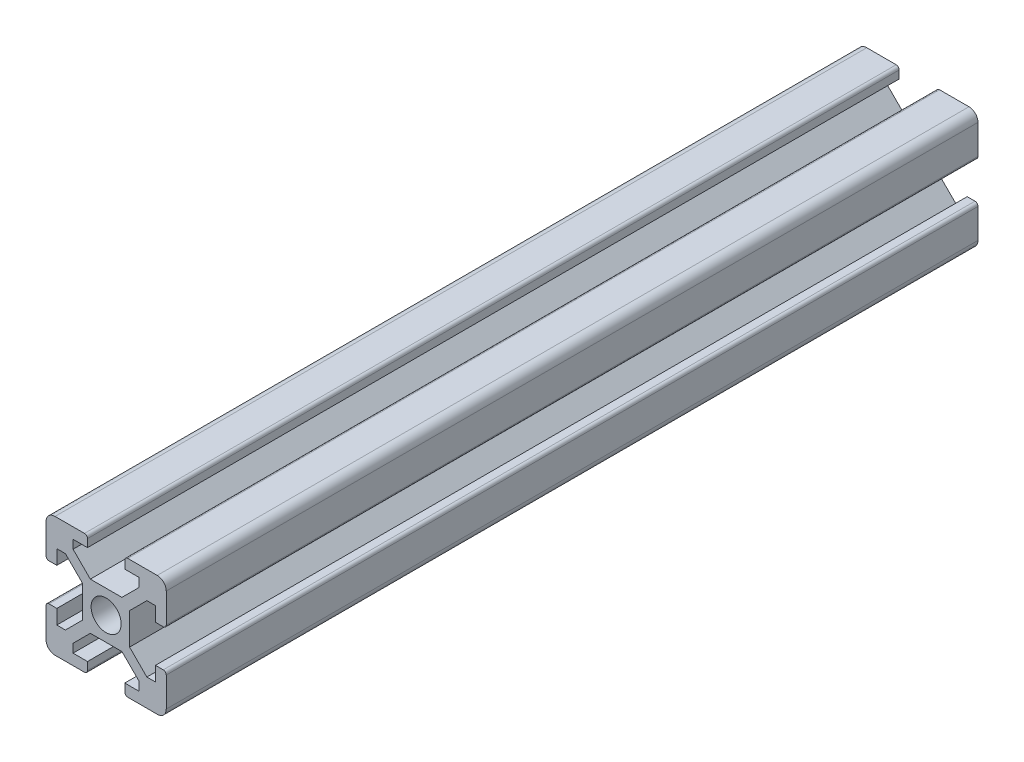
SolidWorks part; units mm, degrees
ref_plane "前视基准面" through (0, 0, 0) normal (0, 0, 1) x (1, 0, 0)
ref_plane "上视基准面" through (0, 0, 0) normal (0, 1, 0) x (1, 0, 0)
ref_plane "右视基准面" through (0, 0, 0) normal (1, 0, 0) x (0, 0, -1)
sketch "草图1" plane through (0, 0, 0) normal (0, 0, 1) x (1, 0, 0)
  line L0 (0, 6.9) -> (0, 0)
  line L1 (20, 20) -> (20, 13.1)
  line L2 (1.8, 15.5) -> (3.2272, 15.5)
  line L3 (4.5, 16.7728) -> (4.5, 18.2)
  line L4 (0, 13.1) -> (0, 20)
  line L5 (6.9, 20) -> (6.9, 18.2)
  line L6 (6.9, 18.2) -> (4.5, 18.2)
  line L7 (13.1, 20) -> (20, 20)
  line L8 (6.9, 20) -> (0, 20)
  line L9 (0, 0) -> (6.9, 0)
  line L10 (13.1, 0) -> (20, 0)
  line L11 (15.5, 18.2) -> (15.5, 16.7728)
  line L12 (16.7728, 15.5) -> (18.2, 15.5)
  line L13 (20, 6.9) -> (20, 0)
  line L14 (1.8, 4.5) -> (3.2272, 4.5)
  line L15 (4.5, 3.2272) -> (4.5, 1.8)
  line L16 (12.6272, 6.1) -> (15.5, 3.2272)
  line L17 (18.2, 4.5) -> (16.7728, 4.5)
  line L18 (15.5, 3.2272) -> (15.5, 1.8)
  line L19 (13.9, 7.3728) -> (16.7728, 4.5)
  line L20 (13.1, 20) -> (13.1, 18.2)
  line L21 (13.1, 18.2) -> (15.5, 18.2)
  line L22 (7.3728, 13.9) -> (12.6272, 13.9)
  line L23 (13.9, 12.6272) -> (13.9, 7.3728)
  line L24 (7.3728, 6.1) -> (12.6272, 6.1)
  line L25 (6.1, 12.6272) -> (6.1, 7.3728)
  line L27 (12.6272, 13.9) -> (15.5, 16.7728)
  line L30 (3.2272, 4.5) -> (6.1, 7.3728)
  line L32 (4.5, 3.2272) -> (7.3728, 6.1)
  line L33 (20, 13.1) -> (18.2, 13.1)
  line L34 (18.2, 13.1) -> (18.2, 15.5)
  line L36 (20, 6.9) -> (18.2, 6.9)
  line L37 (18.2, 6.9) -> (18.2, 4.5)
  line L39 (13.1, 0) -> (13.1, 1.8)
  line L40 (13.1, 1.8) -> (15.5, 1.8)
  line L42 (6.9, 0) -> (6.9, 1.8)
  line L43 (6.9, 1.8) -> (4.5, 1.8)
  line L45 (0, 6.9) -> (1.8, 6.9)
  line L46 (1.8, 6.9) -> (1.8, 4.5)
  line L48 (0, 13.1) -> (1.8, 13.1)
  line L49 (1.8, 13.1) -> (1.8, 15.5)
  line L50 (4.5, 16.7728) -> (7.3728, 13.9)
  line L51 (3.2272, 15.5) -> (6.1, 12.6272)
  line L53 (13.9, 12.6272) -> (16.7728, 15.5)
  line L62 (1.8, 13.1) -> (1.8, 15.5)
  line L63 (0, 13.1) -> (1.8, 13.1)
  line L66 (6.9, 18.2) -> (4.5, 18.2)
  line L67 (6.9, 20) -> (6.9, 18.2)
  line L68 (3.2272, 15.5) -> (1.8, 15.5)
  line L69 (4.5, 18.2) -> (4.5, 16.7728)
  line L75 (4.5, 1.8) -> (4.5, 3.2272)
  line L76 (3.2272, 4.5) -> (1.8, 4.5)
  line L77 (6.9, 0) -> (6.9, 1.8)
  line L78 (6.9, 1.8) -> (4.5, 1.8)
  line L80 (0, 6.9) -> (1.8, 6.9)
  line L81 (1.8, 6.9) -> (1.8, 4.5)
  line L90 (1.8, 6.9) -> (1.8, 4.5)
  line L91 (0, 6.9) -> (1.8, 6.9)
  line L93 (18.2, 6.9) -> (18.2, 4.5)
  line L94 (20, 6.9) -> (18.2, 6.9)
  line L98 (13.1, 1.8) -> (15.5, 1.8)
  line L99 (13.1, 0) -> (13.1, 1.8)
  line L100 (16.7728, 4.5) -> (18.2, 4.5)
  line L101 (15.5, 1.8) -> (15.5, 3.2272)
  line L106 (6.9, 1.8) -> (4.5, 1.8)
  line L107 (6.9, 0) -> (6.9, 1.8)
  line L109 (4.5, 3.2272) -> (4.5, 1.8)
  line L110 (1.8, 4.5) -> (3.2272, 4.5)
  circle A0 centre (10, 10) radius 2.5
extrude "凸台-拉伸1" add sketch "草图1" along normal blind 135 contours L23 L53 L12 L34 L33 L1 L7 L20 L21 L11 L27 L22 L50 L3 L6 L5 L8 L4 L48 L49 L2 L51 L25 L30 L14 L46 L45 L0 L9 L42 L43 L15 L32 L24 L16 L18 L40 L39 L10 L13 L36 L37 L17 L19
fillet "圆角1" radius 1.5 1 edges at (20, 20, 67.5)
fillet "圆角2" radius 1.5 1 edges at (0, 20, 67.5)
fillet "圆角3" radius 1.5 1 edges at (0, 0, 67.5)
fillet "圆角4" radius 1.5 1 edges at (20, 0, 67.5)
fillet "圆角5" radius 0.5 1 edges at (13.1, 20, 67.5)
fillet "圆角6" radius 0.5 1 edges at (6.9, 20, 67.5)
fillet "圆角7" radius 0.5 1 edges at (0, 13.1, 67.5)
fillet "圆角8" radius 0.5 1 edges at (0, 6.9, 67.5)
fillet "圆角9" radius 0.5 1 edges at (6.9, 0, 67.5)
fillet "圆角10" radius 0.5 1 edges at (13.1, 0, 67.5)
fillet "圆角11" radius 0.5 1 edges at (20, 13.1, 67.5)
fillet "圆角12" radius 0.5 1 edges at (20, 6.9, 67.5)
